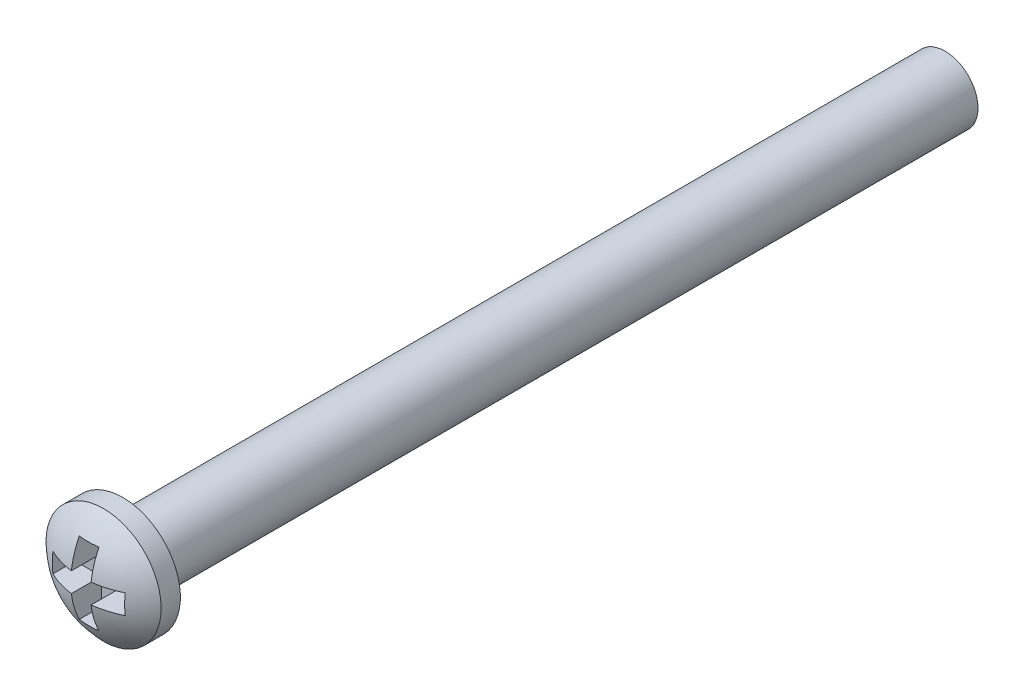
SolidWorks part; units mm, degrees
ref_plane "前视基准面" through (0, 0, 0) normal (0, 0, 1) x (1, 0, 0)
ref_plane "上视基准面" through (0, 0, 0) normal (0, 1, 0) x (1, 0, 0)
ref_plane "右视基准面" through (0, 0, 0) normal (1, 0, 0) x (0, 0, -1)
other "Configuration Table"
sketch "草图1" plane through (0, 0, 0) normal (0, 0, 1) x (1, 0, 0)
  circle A0 centre (0, 0) radius 1
extrude "标准杆径_头下长度" add sketch "草图1" against normal blind 25
sketch "草图2" plane through (0, 0, 0) normal (0, 0, 1) x (1, 0, 0)
  circle A0 centre (0, 0) radius 1.9
sketch "草图4" plane through (0, 0, 0) normal (0, 1, 0) x (1, 0, 0)
  line L0 (0, 0) -> (2.25, 0)
  line L1 (2.25, 0) -> (2.25, -0.1843)
  line L2 (0, -1.2) -> (0, 0)
  line L3 (0, 2) -> (0, -3.2) construction
  arc A0 (2.25, -0.1843) -> (0, -1.2) centre (0, 1.8) cw
sketch "草图5" plane through (0, 0, 0) normal (0, 0, 1) x (1, 0, 0)
  line L0 (-0.3, -1.1) -> (0.3, -1.1)
  line L1 (0.3, -1.1) -> (0.3, -0.3)
  line L2 (0.3, -0.3) -> (1.1, -0.3)
  line L3 (1.1, -0.3) -> (1.1, 0.3)
  line L4 (1.1, 0.3) -> (0.3, 0.3)
  line L5 (0.3, 0.3) -> (0.3, 1.1)
  line L6 (0.3, 1.1) -> (-0.3, 1.1)
  line L7 (-0.3, 1.1) -> (-0.3, 0.3)
  line L8 (-0.3, 0.3) -> (-1.1, 0.3)
  line L9 (-1.1, 0.3) -> (-1.1, -0.3)
  line L10 (-1.1, -0.3) -> (-0.3, -0.3)
  line L11 (-0.3, -0.3) -> (-0.3, -1.1)
sketch "草图6" plane through (0, 0, 0) normal (0, 1, 0) x (1, 0, 0)
  line L0 (0, 0) -> (1.75, 0)
  line L1 (1.75, 0) -> (1.75, -0.5854)
  line L2 (0, -1.3) -> (0, 0)
  line L3 (0, 2) -> (0, -3.3) construction
  arc A0 (1.75, -0.5854) -> (0, -1.3) centre (0, 1.2) cw
revolve "已确认_十字槽盘头" add sketch "草图6" angle 360 about L3
sketch "草图7" plane through (0, 0, 0) normal (0, 0, 1) x (1, 0, 0)
  line L0 (-0.3, -1.1) -> (0.3, -1.1)
  line L1 (0.3, -1.1) -> (0.3, -0.3)
  line L2 (0.3, -0.3) -> (1.1, -0.3)
  line L3 (1.1, -0.3) -> (1.1, 0.3)
  line L4 (1.1, 0.3) -> (0.3, 0.3)
  line L5 (0.3, 0.3) -> (0.3, 1.1)
  line L6 (0.3, 1.1) -> (-0.3, 1.1)
  line L7 (-0.3, 1.1) -> (-0.3, 0.3)
  line L8 (-0.3, 0.3) -> (-1.1, 0.3)
  line L9 (-1.1, 0.3) -> (-1.1, -0.3)
  line L10 (-1.1, -0.3) -> (-0.3, -0.3)
  line L11 (-0.3, -0.3) -> (-0.3, -1.1)
extrude "十字槽_PH1_简化" cut sketch "草图7" against normal blind 0.96 from offset 1.31
